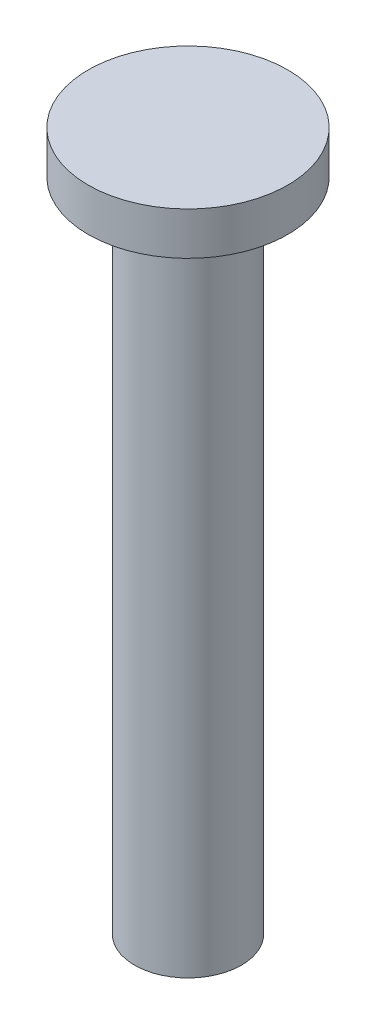
SolidWorks part; units mm, degrees
ref_plane "Front Plane" through (0, 0, 0) normal (0, 0, 1) x (1, 0, 0)
ref_plane "Top Plane" through (0, 0, 0) normal (0, 1, 0) x (1, 0, 0)
ref_plane "Right Plane" through (0, 0, 0) normal (1, 0, 0) x (0, 0, -1)
sketch "Sketch2" plane through (0, 0, 0) normal (0, 0, 1) x (1, 0, 0)
  line L0 (0, 0) -> (0, 24.5)
  line L1 (0, 24.5) -> (3.5, 24.5)
  line L2 (3.5, 24.5) -> (3.5, 23)
  line L3 (3.5, 23) -> (1.875, 23)
  line L4 (1.875, 23) -> (1.875, 0)
  line L5 (1.875, 0) -> (0, 0)
  dimension "D1" = 1.875
  dimension "D2" = 1.5
  dimension "D3" = 23
  dimension "D4" = 3.5
revolve "Revolve1" add sketch "Sketch2" angle 360 about L0
